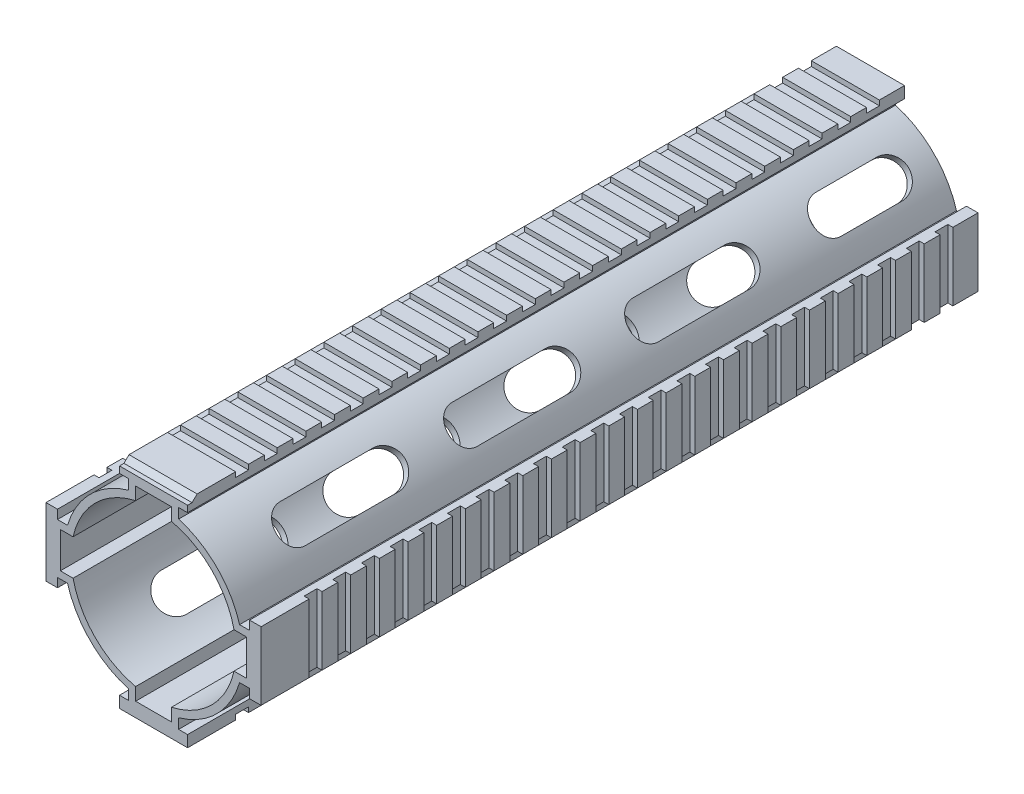
SolidWorks part; units mm, degrees
ref_plane "前视基准面" through (0, 0, 0) normal (0, 0, 1) x (1, 0, 0)
ref_plane "上视基准面" through (0, 0, 0) normal (0, 1, 0) x (1, 0, 0)
ref_plane "右视基准面" through (0, 0, 0) normal (1, 0, 0) x (0, 0, -1)
other "图形1"
sketch "草图1" plane through (0, 0, 0) normal (0, 0, 1) x (1, 0, 0)
  line L2 (-5, -22.4499) -> (-5, -26)
  line L3 (-5, -26) -> (5, -26)
  line L4 (5, -22.4499) -> (5, -26)
  line L5 (-22.4499, 5) -> (-26, 5)
  line L6 (-26, 5) -> (-26, -5)
  line L7 (-22.4499, -5) -> (-26, -5)
  line L8 (5, 22.4499) -> (5, 26)
  line L9 (5, 26) -> (-5, 26)
  line L10 (-5, 22.4499) -> (-5, 26)
  line L11 (22.4499, -5) -> (26, -5)
  line L12 (26, -5) -> (26, 5)
  line L13 (22.4499, 5) -> (26, 5)
  arc A0 (5, -22.4499) -> (22.4499, -5) centre (0, 0) ccw
  arc A1 (-22.4499, -5) -> (-5, -22.4499) centre (0, 0) ccw
  arc A2 (-5, 22.4499) -> (-22.4499, 5) centre (0, 0) ccw
  arc A3 (22.4499, 5) -> (5, 22.4499) centre (0, 0) ccw
  point P22 (0, 0)
  dimension "D1" = 46
  dimension "D3" = 10
  dimension "D4" = 52
  dimension "D2" = 4
sketch "草图2" plane through (0, 0, 0) normal (0, 0, 1) x (1, 0, 0)
  line L2 (-7, -24) -> (-7, -26.8)
  line L4 (7, -24) -> (7, -26.8)
  line L5 (7, -26.8) -> (9.5, -26.8)
  line L6 (-9.5, -26.8) -> (-7, -26.8)
  line L7 (-9.5, -26.8) -> (-9.5, -30)
  line L8 (-9.5, -30) -> (9.5, -30)
  line L9 (9.5, -26.8) -> (9.5, -30)
  line L10 (-24, 7) -> (-26.8, 7)
  line L11 (-26.8, 9.5) -> (-26.8, 7)
  line L12 (-26.8, 9.5) -> (-30, 9.5)
  line L13 (-30, 9.5) -> (-30, -9.5)
  line L14 (-24, -7) -> (-26.8, -7)
  line L15 (-26.8, -7) -> (-26.8, -9.5)
  line L16 (-26.8, -9.5) -> (-30, -9.5)
  line L17 (7, 24) -> (7, 26.8)
  line L18 (9.5, 26.8) -> (7, 26.8)
  line L19 (9.5, 26.8) -> (9.5, 30)
  line L20 (9.5, 30) -> (-9.5, 30)
  line L21 (-7, 24) -> (-7, 26.8)
  line L22 (-7, 26.8) -> (-9.5, 26.8)
  line L23 (-9.5, 26.8) -> (-9.5, 30)
  line L24 (24, -7) -> (26.8, -7)
  line L25 (26.8, -9.5) -> (26.8, -7)
  line L26 (26.8, -9.5) -> (30, -9.5)
  line L27 (30, -9.5) -> (30, 9.5)
  line L28 (24, 7) -> (26.8, 7)
  line L29 (26.8, 7) -> (26.8, 9.5)
  line L30 (26.8, 9.5) -> (30, 9.5)
  line L31 (0, 0) -> (0, -30) construction
  arc A0 (7, -24) -> (24, -7) centre (0, 0) ccw
  arc A1 (24, 7) -> (7, 24) centre (0, 0) ccw
  arc A2 (-7, 24) -> (-24, 7) centre (0, 0) ccw
  arc A3 (-24, -7) -> (-7, -24) centre (0, 0) ccw
  point P39 (0, 0)
  dimension "D1" = 50
  dimension "D3" = 14
  dimension "D4" = 19
  dimension "D5" = 60
  dimension "D6" = 2.8
  dimension "D2" = 4
extrude "凸台-拉伸3" add sketch "草图2" along normal blind 200
extrude "切除-拉伸3" cut sketch "草图1" along normal blind 200 contours A2 L5 L6 L7 A1 L2 L3 L4 A0 L11 L12 L13 A3 L8 L9 L10
ref_plane "基准面1" through (13.725, 13.725, 0) normal (-0.7071, -0.7071, 0) x (0, 0, 1)
ref_plane "基准面2" through (13.725, -13.725, 0) normal (0.7071, -0.7071, 0) x (-0.7071, -0.7071, 0)
sketch "草图5" plane through (13.725, -13.725, 0) normal (0.7071, -0.7071, 0) x (-0.7071, -0.7071, 0)
  line L0 (0, -12) -> (0, -29) construction
  line L1 (0, 0) -> (0, -200) construction
  line L2 (5, -12) -> (5, -29)
  line L3 (-5, -12) -> (-5, -29)
  line L4 (0, -54.5) -> (0, -80) construction
  line L5 (5, -54.5) -> (5, -80)
  line L6 (-5, -54.5) -> (-5, -80)
  line L7 (0, -104.5) -> (0, -130.5) construction
  line L8 (5, -104.5) -> (5, -130.5)
  line L9 (-5, -104.5) -> (-5, -130.5)
  line L10 (0, -152.5) -> (0, -178.5) construction
  line L11 (5, -152.5) -> (5, -178.5)
  line L12 (-5, -152.5) -> (-5, -178.5)
  line L13 (-12.0208, -200) -> (12.0208, -200) construction
  arc A0 (5, -12) -> (-5, -12) centre (0, -12) ccw
  arc A1 (-5, -29) -> (5, -29) centre (0, -29) ccw
  arc A2 (5, -54.5) -> (-5, -54.5) centre (0, -54.5) ccw
  arc A3 (-5, -80) -> (5, -80) centre (0, -80) ccw
  arc A4 (5, -104.5) -> (-5, -104.5) centre (0, -104.5) ccw
  arc A5 (-5, -130.5) -> (5, -130.5) centre (0, -130.5) ccw
  arc A6 (5, -152.5) -> (-5, -152.5) centre (0, -152.5) ccw
  arc A7 (-5, -178.5) -> (5, -178.5) centre (0, -178.5) ccw
  point P5 (0, -20.5)
  point P10 (0, -67.25)
  point P17 (0, -117.5)
  point P24 (0, -165.5)
  dimension "D9" = 5
  dimension "D1" = 21.5
  dimension "D2" = 26
  dimension "D3" = 22
  dimension "D4" = 26
  dimension "D5" = 24.5
  dimension "D6" = 25.5
  dimension "D7" = 12
  dimension "D8" = 17
extrude "切除-拉伸4" cut sketch "草图5" along normal through all both and the other way through all
sketch "草图9" plane through (0, 0, 0) normal (1, 0, 0) x (0, 0, -1)
  line L0 (-200, 30) -> (0, 30) construction
  line L1 (-10.6, 30) -> (-7, 30)
  line L2 (-10.6, 30) -> (-10.6, 28.6)
  line L3 (-10.6, 28.6) -> (-7, 28.6)
  line L4 (-7, 30) -> (-7, 28.6)
  line L5 (0, 24) -> (0, 26.8) construction
  line L10 (-18.6, 30) -> (-15, 30)
  line L11 (-18.6, 30) -> (-18.6, 28.6)
  line L12 (-18.6, 28.6) -> (-15, 28.6)
  line L13 (-15, 30) -> (-15, 28.6)
  line L14 (-26.6, 30) -> (-23, 30)
  line L15 (-26.6, 30) -> (-26.6, 28.6)
  line L16 (-26.6, 28.6) -> (-23, 28.6)
  line L17 (-23, 30) -> (-23, 28.6)
  line L18 (-34.6, 30) -> (-31, 30)
  line L19 (-34.6, 30) -> (-34.6, 28.6)
  line L20 (-34.6, 28.6) -> (-31, 28.6)
  line L21 (-31, 30) -> (-31, 28.6)
  line L22 (-42.6, 30) -> (-39, 30)
  line L23 (-42.6, 30) -> (-42.6, 28.6)
  line L24 (-42.6, 28.6) -> (-39, 28.6)
  line L25 (-39, 30) -> (-39, 28.6)
  line L26 (-50.6, 30) -> (-47, 30)
  line L27 (-50.6, 30) -> (-50.6, 28.6)
  line L28 (-50.6, 28.6) -> (-47, 28.6)
  line L29 (-47, 30) -> (-47, 28.6)
  line L30 (-58.6, 30) -> (-55, 30)
  line L31 (-58.6, 30) -> (-58.6, 28.6)
  line L32 (-58.6, 28.6) -> (-55, 28.6)
  line L33 (-55, 30) -> (-55, 28.6)
  line L34 (-66.6, 30) -> (-63, 30)
  line L35 (-66.6, 30) -> (-66.6, 28.6)
  line L36 (-66.6, 28.6) -> (-63, 28.6)
  line L37 (-63, 30) -> (-63, 28.6)
  line L38 (-74.6, 30) -> (-71, 30)
  line L39 (-74.6, 30) -> (-74.6, 28.6)
  line L40 (-74.6, 28.6) -> (-71, 28.6)
  line L41 (-71, 30) -> (-71, 28.6)
  line L42 (-82.6, 30) -> (-79, 30)
  line L43 (-82.6, 30) -> (-82.6, 28.6)
  line L44 (-82.6, 28.6) -> (-79, 28.6)
  line L45 (-79, 30) -> (-79, 28.6)
  line L46 (-90.6, 30) -> (-87, 30)
  line L47 (-90.6, 30) -> (-90.6, 28.6)
  line L48 (-90.6, 28.6) -> (-87, 28.6)
  line L49 (-87, 30) -> (-87, 28.6)
  line L50 (-98.6, 30) -> (-95, 30)
  line L51 (-98.6, 30) -> (-98.6, 28.6)
  line L52 (-98.6, 28.6) -> (-95, 28.6)
  line L53 (-95, 30) -> (-95, 28.6)
  line L54 (-106.6, 30) -> (-103, 30)
  line L55 (-106.6, 30) -> (-106.6, 28.6)
  line L56 (-106.6, 28.6) -> (-103, 28.6)
  line L57 (-103, 30) -> (-103, 28.6)
  line L58 (-114.6, 30) -> (-111, 30)
  line L59 (-114.6, 30) -> (-114.6, 28.6)
  line L60 (-114.6, 28.6) -> (-111, 28.6)
  line L61 (-111, 30) -> (-111, 28.6)
  line L62 (-122.6, 30) -> (-119, 30)
  line L63 (-122.6, 30) -> (-122.6, 28.6)
  line L64 (-122.6, 28.6) -> (-119, 28.6)
  line L65 (-119, 30) -> (-119, 28.6)
  line L66 (-130.6, 30) -> (-127, 30)
  line L67 (-130.6, 30) -> (-130.6, 28.6)
  line L68 (-130.6, 28.6) -> (-127, 28.6)
  line L69 (-127, 30) -> (-127, 28.6)
  line L70 (-138.6, 30) -> (-135, 30)
  line L71 (-138.6, 30) -> (-138.6, 28.6)
  line L72 (-138.6, 28.6) -> (-135, 28.6)
  line L73 (-135, 30) -> (-135, 28.6)
  line L74 (-146.6, 30) -> (-143, 30)
  line L75 (-146.6, 30) -> (-146.6, 28.6)
  line L76 (-146.6, 28.6) -> (-143, 28.6)
  line L77 (-143, 30) -> (-143, 28.6)
  line L78 (-154.6, 30) -> (-151, 30)
  line L79 (-154.6, 30) -> (-154.6, 28.6)
  line L80 (-154.6, 28.6) -> (-151, 28.6)
  line L81 (-151, 30) -> (-151, 28.6)
  line L82 (-162.6, 30) -> (-159, 30)
  line L83 (-162.6, 30) -> (-162.6, 28.6)
  line L84 (-162.6, 28.6) -> (-159, 28.6)
  line L85 (-159, 30) -> (-159, 28.6)
  line L86 (-170.6, 30) -> (-167, 30)
  line L87 (-170.6, 30) -> (-170.6, 28.6)
  line L88 (-170.6, 28.6) -> (-167, 28.6)
  line L89 (-167, 30) -> (-167, 28.6)
  line L90 (-178.6, 30) -> (-175, 30)
  line L91 (-178.6, 30) -> (-178.6, 28.6)
  line L92 (-178.6, 28.6) -> (-175, 28.6)
  line L93 (-175, 30) -> (-175, 28.6)
  line L94 (-186.6, 30) -> (-183, 30)
  line L95 (-186.6, 30) -> (-186.6, 28.6)
  line L96 (-186.6, 28.6) -> (-183, 28.6)
  line L97 (-183, 30) -> (-183, 28.6)
  line L102 (-194.6, 30) -> (-191, 30) [skipped]
  line L103 (-194.6, 30) -> (-194.6, 28.6) [skipped]
  line L104 (-194.6, 28.6) -> (-191, 28.6) [skipped]
  line L105 (-191, 30) -> (-191, 28.6) [skipped]
  dimension "D1" = 1.4
  dimension "D2" = 7
  dimension "D3" = 3.6
  dimension "D5" = 8
  dimension "D4" = 24
extrude "切除-拉伸5" cut sketch "草图9" against normal through all both and the other way through all
sketch "草图10" plane through (0, 0, 0) normal (1, 0, 0) x (0, 0, -1)
  line L0 (-200, 28.6) -> (-198.75, 28.6)
  line L1 (-200, 26.8) -> (-200, 30) construction
  line L2 (-198.75, 28.6) -> (-197.35, 30)
  line L3 (-200, 30) -> (-186.6, 30) construction
  line L4 (-183, 28.6) -> (-186.6, 28.6) construction
  line L5 (-200, 28.6) -> (-200, 30)
  line L6 (-200, 30) -> (-197.35, 30)
  dimension "D1" = 1.25
  dimension "D2" = 135
extrude "切除-拉伸6" cut sketch "草图10" against normal through all both and the other way through all
pattern_circular "阵列(圆周)8" count 4 over 360 about axis through (0, 0, 0) along (0, 0, 1) of "切除-拉伸4", "切除-拉伸5"
